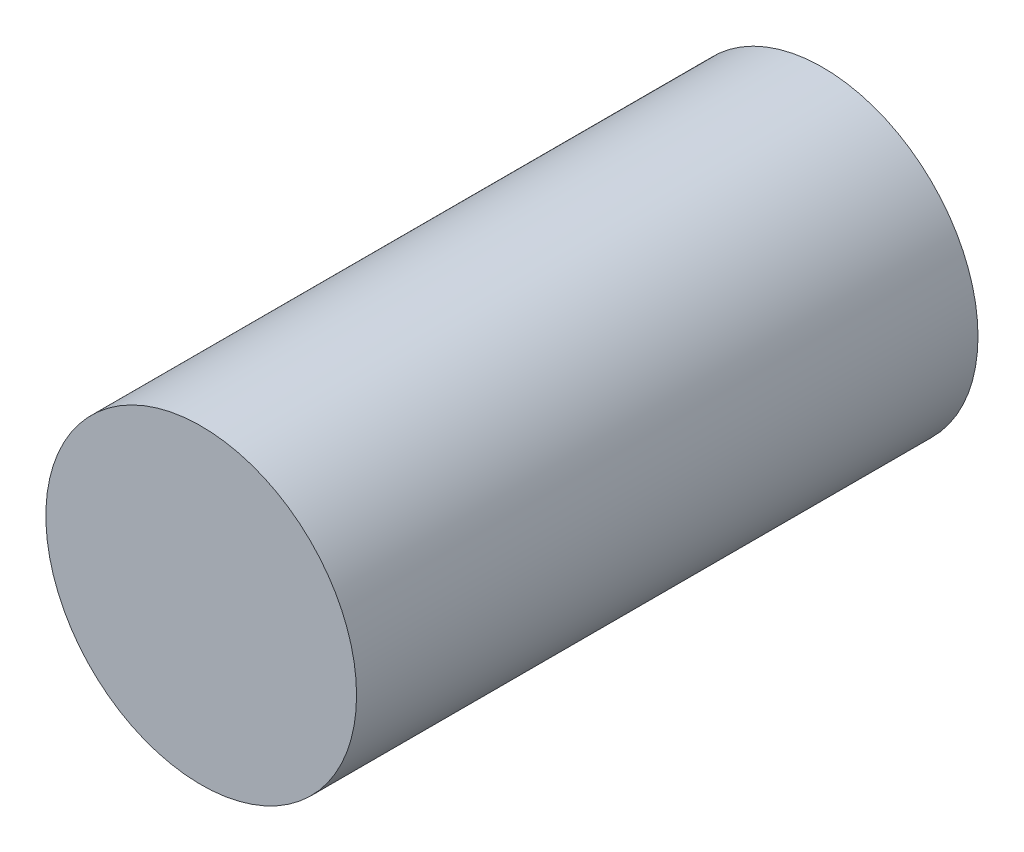
SolidWorks part; units mm, degrees
material "AISI 304"
ref_plane "Front Plane" through (0, 0, 0) normal (0, 0, 1) x (1, 0, 0)
ref_plane "Top Plane" through (0, 0, 0) normal (0, 1, 0) x (1, 0, 0)
ref_plane "Right Plane" through (0, 0, 0) normal (1, 0, 0) x (0, 0, -1)
sketch "Dowel Profile" plane through (0, 0, 0) normal (0, 0, 1) x (1, 0, 0)
  circle A0 centre (0, 0) radius 1.27
  dimension "Dowel Diameter" = 2.54
extrude "Dowel" add sketch "Dowel Profile" along normal mid plane 5.08
